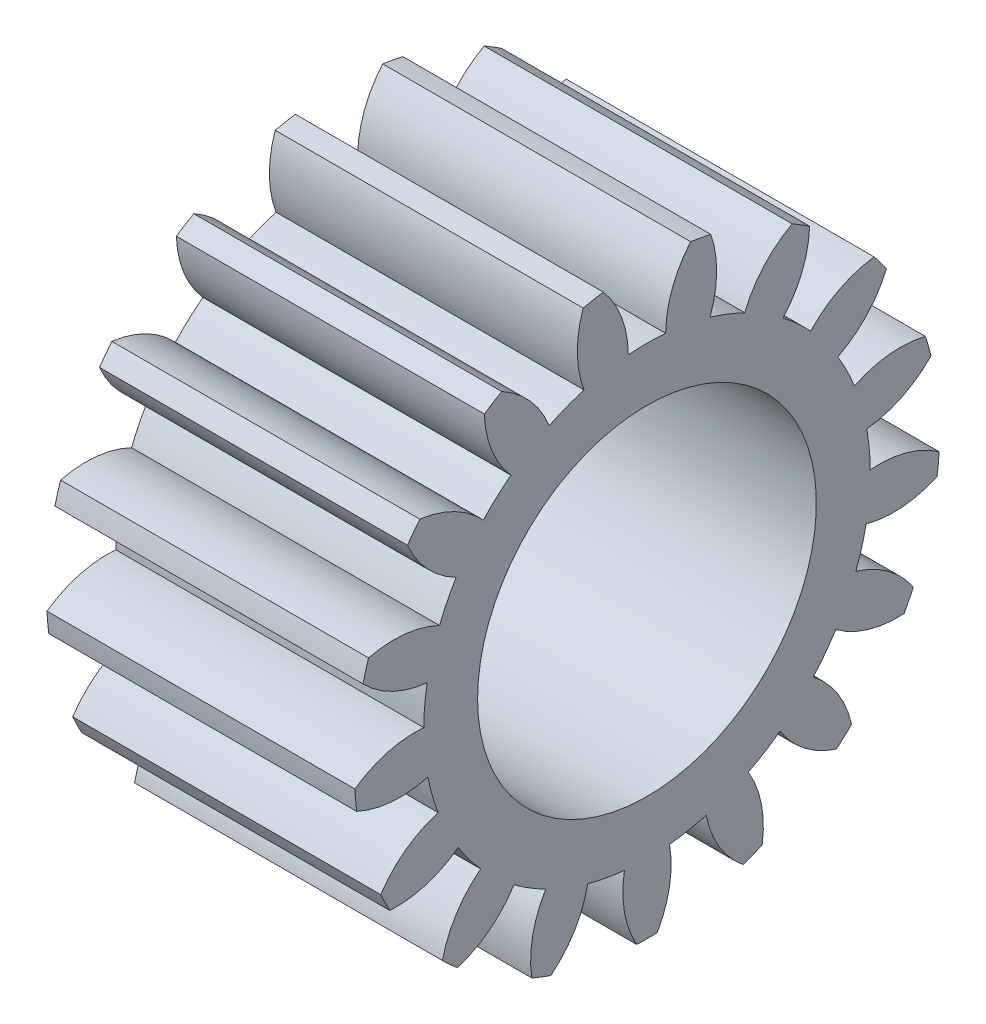
SolidWorks part; units mm, degrees
ref_plane "Plane1" through (0, 0, 0) normal (0, 0, 1) x (1, 0, 0)
ref_plane "Plane2" through (0, 0, 0) normal (0, 1, 0) x (1, 0, 0)
ref_plane "Plane3" through (0, 0, 0) normal (1, 0, 0) x (0, 0, -1)
sketch "HoldingSke" plane through (0, 0, 0) normal (0, 1, 0) x (1, 0, 0)
  line L0 (0, 0) -> (0.9563, -0.2924)
  line L1 (-15, 0) -> (100, 0) construction
  line L2 (0, 0) -> (-2.1039, 2.3779)
  line L3 (0, 0) -> (-11.863, 4.5341)
  line L4 (0, 0) -> (8.2586, 2.5249)
  line L5 (0, 0) -> (-46.8476, -17.4728)
  line L6 (0, 0) -> (-8.2896, -5.593)
  line L7 (-2.1039, 2.3779) -> (8.6586, 51.2059)
  line L8 (-76.2, 54.61) -> (-74.4, 54.61)
  line L9 (-67.7845, 28.3722) -> (-49.3413, 33.142)
  line L10 (-76.2, 71.12) -> (104.1128, 71.12)
  line L11 (0, 0) -> (-10, 0)
  line L12 (-76.2, 101.6) -> (-76.162, 101.6)
  line L13 (24.9733, 27.94) -> (52.9518, 28.4284)
  line L14 (24.9733, 27.94) -> (24.9743, 27.94)
  line L15 (24.9733, 27.94) -> (100.4006, 29.5858)
  line L16 (-63.627, -1) -> (-12.827, -1)
  circle A0 centre (0, 0) radius 5.5
  circle A1 centre (0, 0) radius 7.249
  circle A2 centre (0, 0) radius 37.5
  circle A3 centre (0, 0) radius 5.5
  dimension "MHD" = 14.498
  dimension "Hub_dia" = 75
  dimension "Bore" = 11
  dimension "MBD" = 11
  dimension "Num_teeth" = 17
  dimension "Pitch" = 1
  dimension "Overall_len" = 50
  dimension "Show_teeth" = 17
  dimension "Thickness" = 10
  dimension "OAL" = 50.0001
  dimension "T_dim" = 1.8
  dimension "Ap" = 14.5
  dimension "H" = 19.05
  dimension "Pitch_radius" = 180.3128
  dimension "Width" = 10
  dimension "Backlash" = 0.038
  dimension "Addendum_fac" = 1
  dimension "Dedendum_fac" = 1.25
  dimension "Clearance_fac" = 0.25
  dimension "Dedendum_add" = 0.001
  dimension "Module" = 1
sketch "BasProSke" plane through (0, 0, 0) normal (0, 1, 0) x (1, 0, 0)
  line L0 (-10, 0) -> (60, 0) construction
  line L1 (0, 0) -> (0, 9.5)
  line L2 (0, 0) -> (10, 0)
  line L3 (10, 0) -> (10, 9.5)
  line L4 (10, 9.5) -> (0, 9.5)
  dimension "Thickness" = 10
  dimension "Diameter" = 19
revolve "Base-Revolve" add sketch "BasProSke" angle 360 about L0
sketch "TooCutSke" plane through (0, 0, 0) normal (1, 0, 0) x (0, 0, -1)
  line L1 (0, 0) -> (0, 107) construction
  line L2 (0, 0) -> (-0.8507, 8.4573) construction
  line L3 (0, 0) -> (-3.1126, 16.6509) construction
  line L4 (-0.8507, 8.4573) -> (-1.5563, 8.3254) construction
  arc A0 (0.6054, 7.2237) -> (-0.6054, 7.2237) centre (0, 0) ccw
  arc A1 (1.4366, 9.4164) -> (-1.4366, 9.4164) centre (0, 0) ccw
  circle A2 centre (0, 0) radius 8.5 construction
  circle A3 centre (0, 0) radius 8.2293 construction
  arc A4 (-0.6054, 7.2237) -> (-1.4366, 9.4164) centre (-4.0052, 7.1888) ccw
  arc A5 (1.4366, 9.4164) -> (0.6054, 7.2237) centre (4.0052, 7.1888) ccw
  dimension "Root_dia" = 14.498
  dimension "Overcut_dia" = 19.0508
  dimension "Pitch_dia" = 17
  dimension "Base_dia" = 16.4585
  dimension "Flank_rad" = 3.4
  dimension "Half_ang" = 10.588
  dimension "Half_CT" = 0.7178
extrude "ToothCut" cut sketch "TooCutSke" along normal through all
fillet "Breaks" [suppressed] radius 0.02
fillet "RootFillets" [suppressed] radius 0.251
pattern_circular "TeethCuts" count 17 every 21.176 about axis through (-10, 0, 0) along (1, 0, 0) of "ToothCut", "RootFillets", "Breaks"
sketch "HubNeaOneSke" plane through (0, 0, 0) normal (-1, 0, 0) x (0, 0, 1)
  circle A0 centre (0, 0) radius 7.249
  dimension "Diameter" = 14.498
extrude "HubNearOne" [suppressed] add sketch "HubNeaOneSke" along normal blind 40.0001
sketch "HubNeaBotSke" plane through (0, 0, 0) normal (-1, 0, 0) x (0, 0, 1)
  circle A0 centre (0, 0) radius 7.249
  dimension "Diameter" = 14.498
extrude "HubNearBoth" [suppressed] add sketch "HubNeaBotSke" along normal blind 20
ref_plane "FarPln" through (10, 0, 0) normal (1, 0, 0) x (0, 0, -1)
sketch "HubFarSke" plane through (10, 0, 0) normal (1, 0, 0) x (0, 0, -1)
  circle A0 centre (0, 0) radius 7.249
  dimension "Diameter" = 14.498
extrude "HubFar" [suppressed] add sketch "HubFarSke" along normal blind 20
sketch "BorSke" plane through (0, 0, 0) normal (1, 0, 0) x (0, 0, -1)
  circle A0 centre (0, 0) radius 5.5
  dimension "Diameter" = 11
extrude "Bore" cut sketch "BorSke" along normal mid plane 100.0001
sketch "KeySke" plane through (0, 0, 0) normal (1, 0, 0) x (0, 0, -1)
  line L0 (-2, 0) -> (-2, 7.3)
  line L1 (-2, 7.3) -> (2, 7.3)
  line L2 (2, 7.3) -> (2, 0)
  line L3 (0, 0) -> (0, 34) construction
  line L4 (-2, 0) -> (2, 0)
  dimension "Offset" = 7.3
  dimension "Width" = 4
extrude "Keyway" [suppressed] cut sketch "KeySke" along normal mid plane 100.0001
pattern_circular "Keyway2" [suppressed] count 2 every 90 about axis through (-10, 0, 0) along (1, 0, 0)
equation "' \"Module@HoldingSke\" = 6.35"
equation "' \"Num_teeth@HoldingSke\" = 12"
equation "' \"Ap@HoldingSke\" =  20"
equation "' \"Ap@HoldingSke\" = 20"
equation "' \"Width@HoldingSke\" = 0.5 * 25.4"
equation "' \"Hub_dia@HoldingSke\"= 1 * 25.4"
equation "' \"Hub_dia@HoldingSke\" = 1 * 25.4"
equation "' \"Overall_len@HoldingSke\" = 1.0 * 25.4"
equation "' \"Bore@HoldingSke\" = 0.75 * 25.4"
equation "' \"T_dim@HoldingSke\" = 0.1 * 25.4"
equation "' \"Width@KeySke\" = 0.25 * 25.4"
equation "' \"Show_teeth@HoldingSke\" = 13"
equation "' \"Backlash@HoldingSke\" = 0.009 * 25.4"
equation "' \"Addendum_fac@HoldingSke\" = 1.0"
equation "' \"Dedendum_fac@HoldingSke\" = 1.25"
equation "' \"Dedendum_add@HoldingSke\" = 0.00005 * 25.4"
equation "' \"Clearance_fac@HoldingSke\" = 0.25"
equation "\"Pitch@HoldingSke\" = 1 / \"Module@HoldingSke\""
equation "\"Overcut_dia@TooCutSke\" = (\"Num_teeth@HoldingSke\" + 2 * \"Addendum_fac@HoldingSke\") / \"Pitch@HoldingSke\" + 0.002 * 25.4"
equation "\"Pitch_dia@TooCutSke\" = \"Num_teeth@HoldingSke\" / \"Pitch@HoldingSke\""
equation "\"Base_dia@TooCutSke\" = \"Num_teeth@HoldingSke\" / \"Pitch@HoldingSke\" * cos((\"Ap@HoldingSke\"  * 3.14159265 / 180))"
equation "\"Root_dia@TooCutSke\" = (\"Num_teeth@HoldingSke\" + 2) / \"Pitch@HoldingSke\" - 2 * (\"Addendum_fac@HoldingSke\" + \"Dedendum_fac@HoldingSke\") / \"Pitch@HoldingSke\" - \"Dedendum_add@HoldingSke\" * 2"
equation "\"Half_ang@TooCutSke\" = 180 / \"Num_teeth@HoldingSke\""
equation "\"Half_CT@TooCutSke\" = \"Num_teeth@HoldingSke\" / \"Pitch@HoldingSke\" * sin((3.14159265 / 2 / \"Num_teeth@HoldingSke\")) / 2 - 7 * \"Backlash@HoldingSke\" / 4"
equation "\"Flank_rad@TooCutSke\" = \"Num_teeth@HoldingSke\" / \"Pitch@HoldingSke\" / 5"
equation "\"Radius@RootFillets\" = \"Clearance_fac@HoldingSke\" / \"Pitch@HoldingSke\" + \"Dedendum_add@HoldingSke\""
equation "\"Break_rad@Breaks\" = 0.02 / \"Pitch@HoldingSke\""
equation "\"Thickness@HoldingSke\" = \"Width@HoldingSke\""
equation "\"OAL@HoldingSke\" = \"Thickness@HoldingSke\""
equation "\"MHD@HoldingSke\" = (\"Num_teeth@HoldingSke\" + 2) / \"Pitch@HoldingSke\" - 2 * (\"Addendum_fac@HoldingSke\" + \"Dedendum_fac@HoldingSke\")  / \"Pitch@HoldingSke\" - \"Dedendum_add@HoldingSke\" * 2"
equation "\"MBD@HoldingSke\" = (\"Num_teeth@HoldingSke\" + 2) / \"Pitch@HoldingSke\" - 2 * (\"Addendum_fac@HoldingSke\" + \"Dedendum_fac@HoldingSke\")  / \"Pitch@HoldingSke\" - \"Dedendum_add@HoldingSke\" * 2 - 0.002 * 25.4"
equation "\"MHD@HoldingSke\" = ((sgn( \"MHD@HoldingSke\" - \"Hub_dia@HoldingSke\" )-1)*( \"MHD@HoldingSke\" - \"Hub_dia@HoldingSke\" ))/-2+ \"Hub_dia@HoldingSke\""
equation "\"MBD@HoldingSke\" = ((sgn( \"MBD@HoldingSke\" - \"Bore@HoldingSke\" )-1)*( \"MBD@HoldingSke\" - \"Bore@HoldingSke\" ))/-2+ \"Bore@HoldingSke\""
equation "\"OAL@HoldingSke\" = ((sgn( \"OAL@HoldingSke\" - \"Overall_len@HoldingSke\" )+1)*( \"OAL@HoldingSke\" - \"Overall_len@HoldingSke\" ))/2 + \"Overall_len@HoldingSke\" + 0.000002 * 25.4"
equation "\"Num_teeth@TeethCuts\" = int( \"Show_teeth@HoldingSke\" ) + 1"
equation "\"Num_teeth@TeethCuts\" = ((sgn( \"Num_teeth@TeethCuts\" - \"Num_teeth@HoldingSke\" )-1)*( \"Num_teeth@TeethCuts\" - \"Num_teeth@HoldingSke\" ))/-2+ \"Num_teeth@HoldingSke\""
equation "\"Num_teeth@TeethCuts\" = ((sgn( \"Num_teeth@TeethCuts\" - 2.0)+1)*( \"Num_teeth@TeethCuts\" - 2.0))/2 +2.0"
equation "\"Angle@TeethCuts\" = 360.0 / \"Num_teeth@HoldingSke\""
equation "\"Diameter@BasProSke\" = (\"Num_teeth@HoldingSke\" + 2 * \"Addendum_fac@HoldingSke\") / \"Pitch@HoldingSke\""
equation "\"Thickness@BasProSke\"  = \"Thickness@HoldingSke\""
equation "' \"Fillet_rad@BasProSke\" =  \"Thickness@HoldingSke\" * 0.05"
equation "' \"Fillet_rad@BasProSke\" = \"Thickness@HoldingSke\" * 0.05"
equation "\"MHD@HoldingSke\" = ((sgn( \"MHD@HoldingSke\" - \"Root_dia@TooCutSke\" )-1)*( \"MHD@HoldingSke\" - \"Root_dia@TooCutSke\" ))/-2+ \"Root_dia@TooCutSke\""
equation "\"Diameter@HubNeaOneSke\" = \"MHD@HoldingSke\""
equation "\"Length@HubNearOne\" = \"OAL@HoldingSke\" - \"Thickness@BasProSke\""
equation "\"Diameter@HubNeaBotSke\" = \"MHD@HoldingSke\""
equation "\"Length@HubNearBoth\" = ( \"OAL@HoldingSke\" - \"Thickness@BasProSke\" ) / 2.0"
equation "\"Thickness@FarPln\" = \"Thickness@BasProSke\""
equation "\"Diameter@HubFarSke\" = \"MHD@HoldingSke\""
equation "\"Length@HubFar\" = ( \"OAL@HoldingSke\" - \"Thickness@BasProSke\" ) / 2.0"
equation "\"Diameter@BorSke\" = \"MBD@HoldingSke\""
equation "\"D1@Bore\" = \"OAL@HoldingSke\" * 2.0"
equation "\"D1@Keyway\" = \"OAL@HoldingSke\" * 2.0"
equation "\"Offset@KeySke\" = \"T_dim@HoldingSke\" + \"MBD@HoldingSke\" / 2.0"
